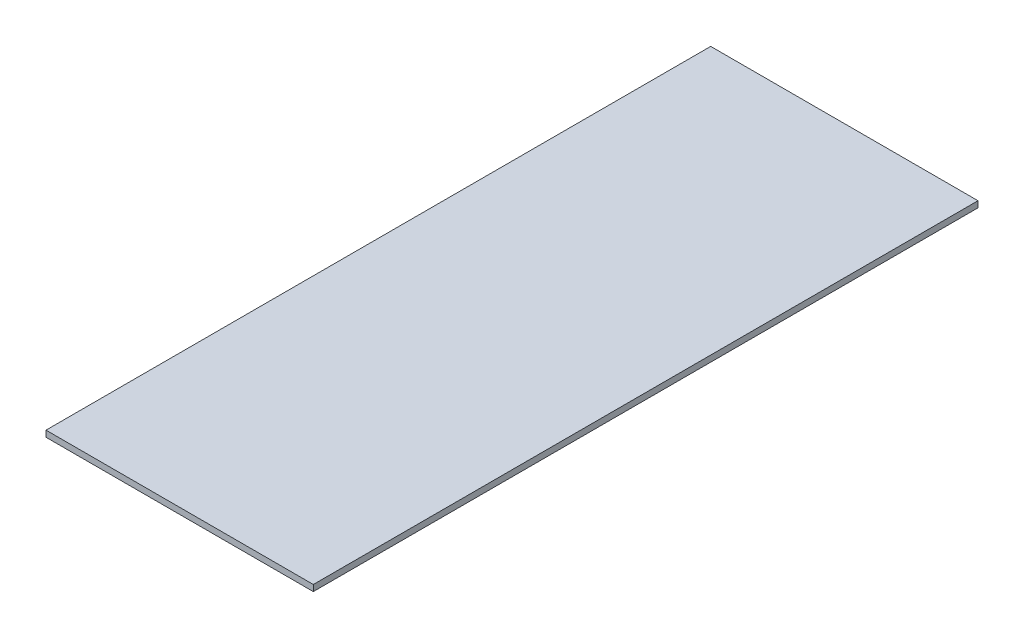
SolidWorks part; units mm, degrees
ref_plane "Front Plane" through (0, 0, 0) normal (0, 0, 1) x (1, 0, 0)
ref_plane "Top Plane" through (0, 0, 0) normal (0, 1, 0) x (1, 0, 0)
ref_plane "Right Plane" through (0, 0, 0) normal (1, 0, 0) x (0, 0, -1)
sketch "Sketch1" plane through (0, 0, 0) normal (0, 1, 0) x (1, 0, 0)
  line L1 (-120.65, -300) -> (120.65, -300)
  line L2 (-120.65, -300) -> (-120.65, 300)
  line L3 (-120.65, 300) -> (120.65, 300)
  line L4 (120.65, -300) -> (120.65, 300)
  line L5 (-120.65, -300) -> (120.65, 300) construction
  line L6 (-120.65, 300) -> (120.65, -300) construction
  point P0 (0, 0)
  dimension "D1" = 241.3
  dimension "D2" = 600
extrude "Boss-Extrude1" add sketch "Sketch1" along normal blind 5.588
